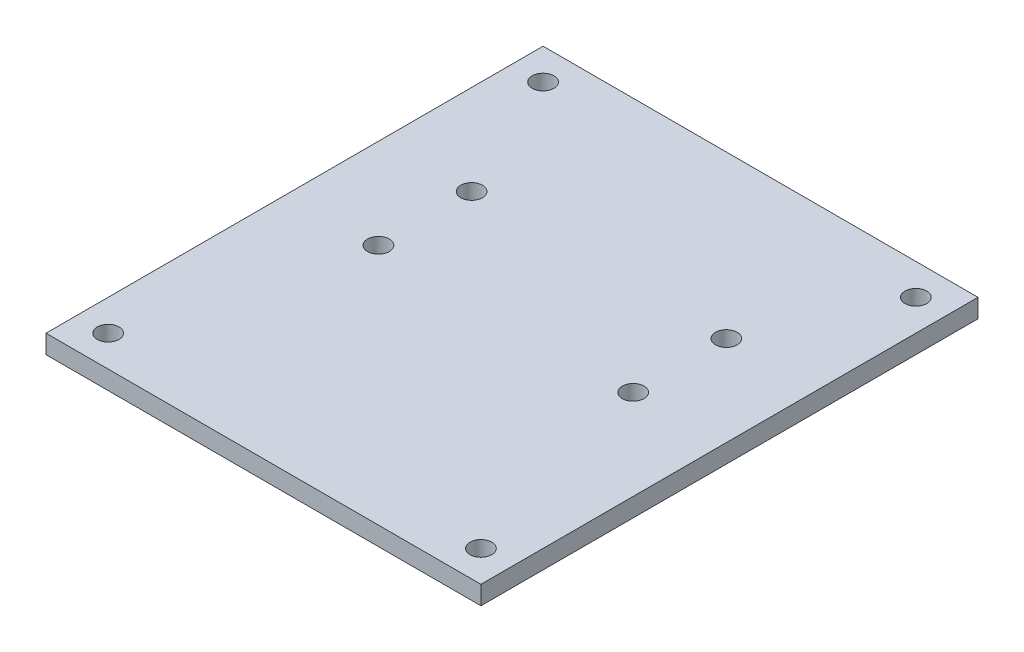
SolidWorks part; units mm, degrees
material "Acrílico (Impacto medio-alto)"
ref_plane "Front Plane" through (0, 0, 0) normal (0, 0, 1) x (1, 0, 0)
ref_plane "Top Plane" through (0, 0, 0) normal (0, 1, 0) x (1, 0, 0)
ref_plane "Right Plane" through (0, 0, 0) normal (1, 0, 0) x (0, 0, -1)
sketch "Sketch1" plane through (0, 0, 0) normal (0, 1, 0) x (1, 0, 0)
  line L0 (50, 0) -> (0, 0) construction
  line L1 (-35, -46.5) -> (35, -46.5)
  line L2 (-35, -46.5) -> (-35, 33.5)
  line L3 (-35, 33.5) -> (35, 33.5)
  line L4 (35, -46.5) -> (35, 33.5)
  line L7 (-50, -50) -> (50, -50) construction
  line L8 (-50, -50) -> (-50, 50) construction
  line L9 (-50, 50) -> (50, 50) construction
  line L10 (50, -50) -> (50, 50) construction
  line L11 (0, 50) -> (0, 0) construction
  line L12 (-20.5, 33.5) -> (-20.5, -49.2188) construction
  line L13 (-35, 0) -> (35, 0) construction
  line L14 (-35, 7.5) -> (35, 7.5) construction
  circle A0 centre (-20.5, 7.5) radius 1.75
  circle A1 centre (-20.5, -7.5) radius 1.75
  circle A2 centre (20.5, -7.5) radius 1.75
  circle A3 centre (20.5, 7.5) radius 1.75
  point P0 (0, 0)
  point P6 (0, 0)
  point P16 (-20.5, 7.5)
  dimension "D7" = 3.5
  dimension "D1" = 70
  dimension "D2" = 80
  dimension "D3" = 100
  dimension "D4" = 100
  dimension "D5" = 20.5
  dimension "D6" = 26
  dimension "D8" = 7.5
  dimension "D9" = 35
  dimension "D10" = 20.5
extrude "Boss-Extrude1" add sketch "Sketch1" along normal blind 3
sketch "Sketch2" plane through (0, 3, 0) normal (0, 1, 0) x (1, 0, 0)
  line L0 (35, 33.5) -> (-35, 33.5) construction
  line L1 (35, -46.5) -> (35, 33.5) construction
  line L2 (0, 33.5) -> (0, -46.5) construction
  line L4 (-35, -6.5) -> (35, -6.5) construction
  line L5 (-35, 33.5) -> (-35, -46.5) construction
  line L6 (-35, -46.5) -> (35, -46.5) construction
  circle A0 centre (30, 28.5) radius 1.75
  circle A1 centre (-30, 28.5) radius 1.75
  circle A2 centre (30, -41.5) radius 1.75
  circle A3 centre (-30, -41.5) radius 1.75
  point P9 (0, 0)
  dimension "D1" = 3.5
  dimension "D2" = 5
  dimension "D3" = 5
extrude "Cut-Extrude1" cut sketch "Sketch2" against normal blind 3
